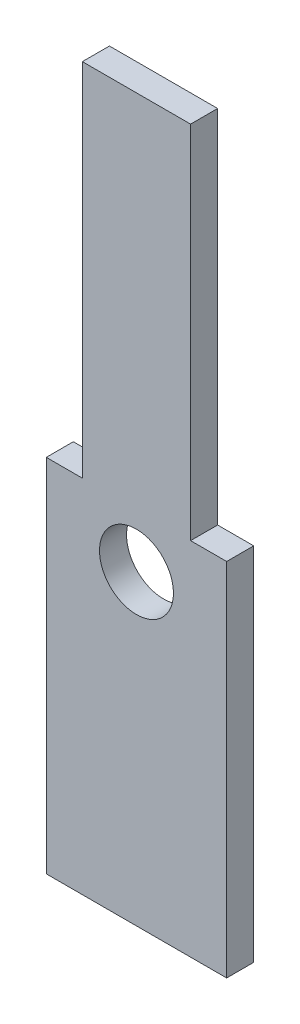
SolidWorks part; units mm, degrees
ref_plane "Front Plane" through (0, 0, 0) normal (0, 0, 1) x (1, 0, 0)
ref_plane "Top Plane" through (0, 0, 0) normal (0, 1, 0) x (1, 0, 0)
ref_plane "Right Plane" through (0, 0, 0) normal (1, 0, 0) x (0, 0, -1)
sketch "Sketch1" plane through (0, 0, 0) normal (0, 0, 1) x (1, 0, 0)
  line L1 (-10, 0) -> (10, 0)
  line L2 (-10, 0) -> (-10, 40)
  line L3 (-10, 40) -> (10, 40)
  line L4 (10, 0) -> (10, 40)
  point P4 (0, 0)
  dimension "D1" = 20
  dimension "D2" = 40
extrude "Boss-Extrude1" add sketch "Sketch1" against normal blind 3
sketch "Sketch2" plane through (0, 0, 0) normal (0, 0, 1) x (1, 0, 0)
  line L0 (10, 40) -> (-10, 40) construction
  circle A0 centre (0, 34) radius 4.1
  point P2 (0, 0)
  dimension "D2" = 8.2
  dimension "D1" = 6
extrude "Cut-Extrude1" cut sketch "Sketch2" against normal blind 3
sketch "Sketch3" plane through (0, 40, 0) normal (0, 1, 0) x (1, 0, 0)
  line L0 (10, 3) -> (-10, 3) construction
  line L1 (-6, 3) -> (6, 3)
  line L2 (-6, 3) -> (-6, 0)
  line L3 (-6, 0) -> (6, 0)
  line L4 (6, 3) -> (6, 0)
  line L5 (10, 0) -> (-10, 0) construction
  point P8 (0, 3)
  dimension "D1" = 12
extrude "Boss-Extrude2" add sketch "Sketch3" along normal blind 40
